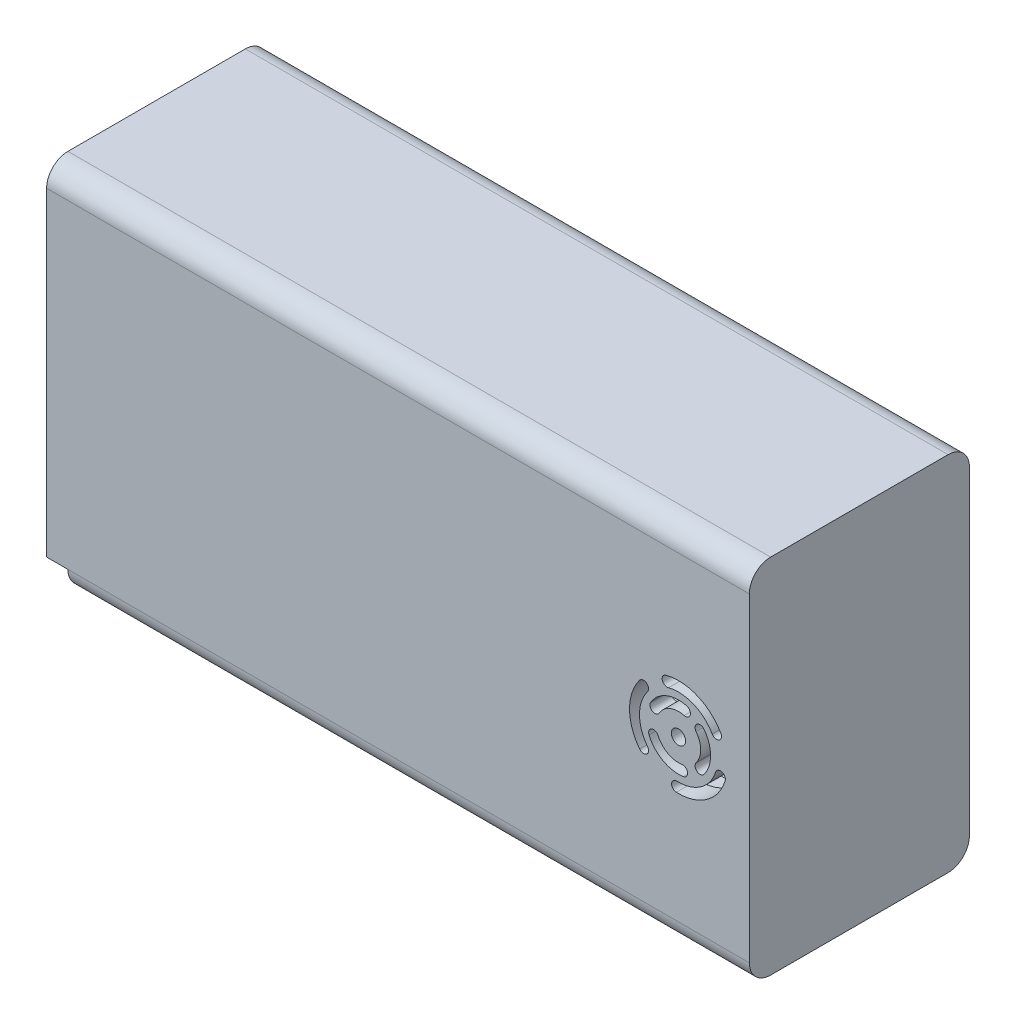
SolidWorks part; units mm, degrees
ref_plane "Front Plane" through (0, 0, 0) normal (0, 0, 1) x (1, 0, 0)
ref_plane "Top Plane" through (0, 0, 0) normal (0, 1, 0) x (1, 0, 0)
ref_plane "Right Plane" through (0, 0, 0) normal (1, 0, 0) x (0, 0, -1)
sketch "Sketch1" plane through (0, 0, 0) normal (0, 0, 1) x (1, 0, 0)
  line L1 (-49.5, 25.5) -> (49.5, 25.5)
  line L2 (-49.5, 25.5) -> (-49.5, -25.5)
  line L3 (-49.5, -25.5) -> (49.5, -25.5)
  line L4 (49.5, 25.5) -> (49.5, -25.5)
  line L5 (-49.5, 25.5) -> (49.5, -25.5) construction
  line L6 (-49.5, -25.5) -> (49.5, 25.5) construction
  point P0 (0, 0)
  dimension "D1" = 51
  dimension "D2" = 99
extrude "Boss-Extrude2" add sketch "Sketch1" along normal blind 31
sketch "Sketch3" plane through (-49.5, 0, 0) normal (-1, 0, 0) x (0, 0, 1)
  line L0 (31, -25.5) -> (0, -25.5) construction
  line L1 (3, 0.6165) -> (3, -22.5)
  line L2 (3, -22.5) -> (28, -22.5)
  line L3 (28, -22.5) -> (28, 22.5)
  line L4 (28, 22.5) -> (3, 22.5)
  line L5 (3, 22.5) -> (3, 0.6165)
  line L6 (31, 25.5) -> (0, 25.5) construction
  line L7 (31, 25.5) -> (31, -25.5) construction
  line L8 (0, 25.5) -> (0, -25.5) construction
  dimension "D1" = 3
  dimension "D2" = 3
  dimension "D3" = 3
  dimension "D4" = 3
extrude "Cut-Extrude1" cut sketch "Sketch3" against normal blind 96
sketch "Sketch4" plane through (0, -25.5, 0) normal (0, -1, 0) x (1, 0, 0)
  line L0 (-49.5, 31) -> (-46.5, 31)
  line L1 (-49.5, 31) -> (49.5, 31) construction
  line L2 (-46.5, 31) -> (-46.5, 0)
  line L3 (-49.5, 0) -> (49.5, 0) construction
  line L4 (-46.5, 0) -> (-49.5, 0)
  line L5 (-49.5, 0) -> (-49.5, 31)
extrude "Cut-Extrude2" cut sketch "Sketch4" against normal blind 3
sketch "Sketch6" plane through (-46.5, 0, 0) normal (-1, 0, 0) x (0, 0, 1)
  line L0 (15.5, -22.5) -> (15.5, 22.5) construction
  line L1 (3, -22.5) -> (28, -22.5) construction
  line L2 (28, 22.5) -> (3, 22.5) construction
  line L3 (15.5, -22.5) -> (16.8, -22.5)
  line L4 (16.8, -22.5) -> (18.8, -22.5)
  line L5 (18.8, -22.5) -> (18.8, -20.5)
  line L6 (18.8, -20.5) -> (16.8, -20.5)
  line L7 (16.8, -20.5) -> (16.8, -22.5)
  line L8 (14.2, -20.5) -> (14.2, -22.5)
  line L9 (12.2, -20.5) -> (14.2, -20.5)
  line L10 (12.2, -22.5) -> (12.2, -20.5)
  line L11 (14.2, -22.5) -> (12.2, -22.5)
  line L12 (0, 0) -> (24.4471, 0) construction
  line L13 (14.2, 22.5) -> (12.2, 22.5)
  line L14 (12.2, 22.5) -> (12.2, 20.5)
  line L15 (12.2, 20.5) -> (14.2, 20.5)
  line L16 (14.2, 20.5) -> (14.2, 22.5)
  line L17 (16.8, 20.5) -> (16.8, 22.5)
  line L18 (18.8, 20.5) -> (16.8, 20.5)
  line L19 (18.8, 22.5) -> (18.8, 20.5)
  line L20 (16.8, 22.5) -> (18.8, 22.5)
  line L21 (15.5, 22.5) -> (16.8, 22.5)
  line M14 (28, -22.5) -> (3, -22.5)
extrude "Boss-Extrude3" add sketch "Sketch6" against normal blind 96 contours L10 L8 L9 M14 | L6 L7 L5 M14 | L15 L16 L13 L14 | L20 L17 L18 L19
sketch "Sketch7" plane through (0, -22.5, 0) normal (0, -1, 0) x (1, 0, 0)
  line L0 (-49.5, 28) -> (-48.5551, 28)
  line L1 (-46.5, 28) -> (-49.5, 28) construction
  line L2 (-48.5551, 28) -> (-48.5551, 29)
  line L3 (-48.5551, 29) -> (-47.5551, 29)
  line L4 (-47.5551, 29) -> (-47.5551, 28)
  line L5 (46.5, 28) -> (-49.5, 28) construction
  line L6 (-47.5551, 28) -> (-48.5551, 28)
  line L7 (-49.5, 15.5) -> (-38.7311, 15.5) construction
  line L8 (-49.5, 28) -> (-49.5, 3) construction
  line L9 (-47.5551, 3) -> (-48.5551, 3)
  line L10 (-47.5551, 2) -> (-47.5551, 3)
  line L11 (-48.5551, 2) -> (-47.5551, 2)
  line L12 (-48.5551, 3) -> (-48.5551, 2)
  line L13 (-49.5, 3) -> (-48.5551, 3)
  line M6 (-49.5, 28) -> (-46.5, 28)
  dimension "D1" = 1
extrude "Cut-Extrude3" cut sketch "Sketch7" against normal blind 45 contours L4 L3 L2 M6 | L9 L12 L11 L10
fillet "Fillet1" radius 3 4 edges at (0, 25.5, 31) (1.5, -25.5, 31) (1.5, -25.5, 0) (0, 25.5, 0)
sketch "Sketch8" plane through (0, 0, 31) normal (0, 0, 1) x (1, 0, 0)
  line L0 (49.5, 0) -> (46.5, 0) construction
  line L1 (49.5, -22.5) -> (49.5, 22.5) construction
  line L2 (46.5, 0) -> (46.5, -34.082) construction
sketch "Sketch9" plane through (0, 0, 28) normal (0, 0, -1) x (-1, 0, 0)
  line L0 (-46.5, 0) -> (-32.4364, 0) construction
  line L1 (31.9682, -7.5) -> (46.9682, 7.5) construction
  line L2 (46.9682, -7.5) -> (31.9682, 7.5) construction
  line L3 (39.4682, -13.2796) -> (39.4682, 13.2796) construction
  line L4 (39.4682, 0) -> (32.0276, -8.8673) construction
  line L5 (39.4682, 0) -> (30.6584, 10.4992) construction
  line L6 (39.4682, 0) -> (29.0284, -4.8681) construction
  line L7 (39.4682, 0) -> (29.0284, 4.8681) construction
  line L8 (39.4682, 0) -> (48.2781, 10.4992) construction
  line L9 (39.4682, 0) -> (49.908, 4.8681) construction
  line L10 (39.4682, 0) -> (49.908, -4.8681) construction
  line L11 (39.4682, 0) -> (46.9088, -8.8673) construction
  line L12 (39.4682, 0) -> (42.9165, -12.8691) construction
  line L13 (39.4682, 0) -> (36.0199, -12.8691) construction
  line L14 (39.4682, 0) -> (42.9165, 12.8691) construction
  line L15 (39.4682, 0) -> (36.0199, 12.8691) construction
  line L16 (39.4682, 0) -> (33.744, 10.9961) construction
  line L17 (39.4682, 0) -> (45.1924, 10.9961) construction
  line L18 (39.4682, 0) -> (42.9165, -12.8691) construction
  line L19 (39.4682, 0) -> (33.744, -10.9961) construction
  line L20 (39.4682, 0) -> (45.1924, 10.9961) construction
  line L21 (39.4682, 0) -> (33.744, -10.9961) construction
  line L22 (39.4682, 0) -> (49.6763, -2.2631) construction
  line L23 (39.4682, 0) -> (47.8665, -6.4442) construction
  line L24 (39.4682, 0) -> (31.6838, 5.9732) construction
  line L25 (39.4682, 0) -> (37.2138, -1.7299) construction
  line L26 (39.4682, 0) -> (48.9178, 2.0949) construction
  line L27 (39.4682, 0) -> (49.4833, 1.0968) construction
  line L28 (39.4682, 0) -> (48.4675, 6.9054) construction
  line L29 (39.4682, 0) -> (31.4522, 1.7771) construction
  line L30 (-47.0152, -7.4485) -> (-32.0152, 7.5515) construction
  line L31 (-32.0152, -7.4485) -> (-47.0152, 7.5515) construction
  line L32 (-39.5152, -13.2282) -> (-39.5152, 13.3311) construction
  line L33 (-39.5152, 0.0515) -> (-46.9557, -8.8159) construction
  line L34 (-39.5152, 0.0515) -> (-48.325, 10.5506) construction
  line L35 (-39.5152, 0.0515) -> (-49.955, -4.8167) construction
  line L36 (-39.5152, 0.0515) -> (-49.955, 4.9196) construction
  line L37 (-39.5152, 0.0515) -> (-30.7053, 10.5506) construction
  line L38 (-39.5152, 0.0515) -> (-29.0754, 4.9196) construction
  line L39 (-39.5152, 0.0515) -> (-29.0754, -4.8167) construction
  line L40 (-39.5152, 0.0515) -> (-32.0746, -8.8159) construction
  line L41 (-39.5152, 0.0515) -> (-36.0669, -12.8177) construction
  line L42 (-39.5152, 0.0515) -> (-42.9635, -12.8177) construction
  line L43 (-39.5152, 0.0515) -> (-36.0669, 12.9206) construction
  line L44 (-39.5152, 0.0515) -> (-42.9635, 12.9206) construction
  line L45 (-39.5152, 0.0515) -> (-45.2394, 11.0475) construction
  line L46 (-39.5152, 0.0515) -> (-33.791, 11.0475) construction
  line L47 (-39.5152, 0.0515) -> (-36.0669, -12.8177) construction
  line L48 (-39.5152, 0.0515) -> (-45.2394, -10.9446) construction
  line L49 (-39.5152, 0.0515) -> (-33.791, 11.0475) construction
  line L50 (-39.5152, 0.0515) -> (-45.2394, -10.9446) construction
  line L51 (-39.5152, 0.0515) -> (-29.3071, -2.2116) construction
  line L52 (-39.5152, 0.0515) -> (-31.1169, -6.3928) construction
  line L53 (-39.5152, 0.0515) -> (-47.2996, 6.0247) construction
  line L54 (-39.5152, 0.0515) -> (-41.7696, -1.6784) construction
  line L55 (-39.5152, 0.0515) -> (-30.0656, 2.1464) construction
  line L56 (-39.5152, 0.0515) -> (-29.5001, 1.1483) construction
  line L57 (-39.5152, 0.0515) -> (-30.5159, 6.9568) construction
  line L58 (-39.5152, 0.0515) -> (-47.5312, 1.8286) construction
  circle A0 centre (39.4682, 0) radius 0.5
  circle A1 centre (39.4682, 0) radius 2
  circle A2 centre (39.4682, 0) radius 2.5
  circle A3 centre (39.4682, 0) radius 1.5
  circle A4 centre (39.4682, 0) radius 1
  arc A5 (36.4314, 2.3302) -> (36.4314, -2.3302) centre (39.4682, 0) ccw construction
  arc A6 (35.876, 2.7564) -> (35.876, -2.7564) centre (39.4682, 0) ccw
  arc A7 (36.9867, 1.9041) -> (36.9867, -1.9041) centre (39.4682, 0) ccw
  arc A8 (36.9867, 1.9041) -> (35.876, 2.7564) centre (36.4314, 2.3302) ccw
  arc A9 (35.876, -2.7564) -> (36.9867, -1.9041) centre (36.4314, -2.3302) ccw
  arc A10 (38.4775, 3.6974) -> (42.7832, 1.9139) centre (39.4682, 0) cw construction
  arc A11 (38.2963, 4.3735) -> (43.3894, 2.2639) centre (39.4682, 0) cw
  arc A12 (38.6587, 3.0212) -> (42.177, 1.5639) centre (39.4682, 0) cw
  arc A13 (38.6587, 3.0212) -> (38.2963, 4.3735) centre (38.4775, 3.6974) cw
  arc A14 (43.3894, 2.2639) -> (42.177, 1.5639) centre (42.7832, 1.9139) cw
  arc A15 (38.8859, -3.7833) -> (42.9719, -1.5416) centre (39.4682, 0) ccw construction
  arc A16 (38.7794, -4.4751) -> (43.6126, -1.8236) centre (39.4682, 0) ccw
  arc A17 (38.9924, -3.0914) -> (42.3311, -1.2597) centre (39.4682, 0) ccw
  arc A18 (38.9924, -3.0914) -> (38.7794, -4.4751) centre (38.8859, -3.7833) ccw
  arc A19 (43.6126, -1.8236) -> (42.3311, -1.2597) centre (42.9719, -1.5416) ccw
  arc A20 (44.382, 3.7704) -> (44.382, -3.7704) centre (39.4682, 0) cw construction
  arc A21 (44.9373, -4.1966) -> (44.9373, 4.1966) centre (39.4682, 0) ccw
  arc A22 (43.8266, -3.3443) -> (43.8266, 3.3443) centre (39.4682, 0) ccw
  arc A23 (43.8266, -3.3443) -> (44.9373, -4.1966) centre (44.382, -3.7704) ccw
  arc A24 (44.9373, 4.1966) -> (43.8266, 3.3443) centre (44.382, 3.7704) ccw
  arc A25 (33.5612, -1.8625) -> (39.7384, -6.1877) centre (39.4682, 0) ccw construction
  arc A26 (39.7689, -6.8871) -> (32.8936, -2.073) centre (39.4682, 0) cw
  arc A27 (39.7078, -5.4884) -> (34.2288, -1.652) centre (39.4682, 0) cw
  arc A28 (39.7078, -5.4884) -> (39.7689, -6.8871) centre (39.7384, -6.1877) cw
  arc A29 (32.8936, -2.073) -> (34.2288, -1.652) centre (33.5612, -1.8625) cw
  arc A30 (34.1044, 3.0968) -> (41.0712, 5.9826) centre (39.4682, 0) cw construction
  arc A31 (41.2524, 6.6587) -> (33.4981, 3.4468) centre (39.4682, 0) ccw
  arc A32 (40.8901, 5.3064) -> (34.7106, 2.7468) centre (39.4682, 0) ccw
  arc A33 (40.8901, 5.3064) -> (41.2524, 6.6587) centre (41.0712, 5.9826) ccw
  arc A34 (33.4981, 3.4468) -> (34.7106, 2.7468) centre (34.1044, 3.0968) ccw
  circle A35 centre (-39.5152, 0.0515) radius 0.5
  circle A36 centre (-39.5152, 0.0515) radius 2
  circle A37 centre (-39.5152, 0.0515) radius 2.5
  circle A38 centre (-39.5152, 0.0515) radius 1.5
  circle A39 centre (-39.5152, 0.0515) radius 1
  arc A40 (-42.552, 2.3817) -> (-42.552, -2.2788) centre (-39.5152, 0.0515) ccw construction
  arc A41 (-43.1073, 2.8078) -> (-43.1073, -2.7049) centre (-39.5152, 0.0515) ccw
  arc A42 (-41.9967, 1.9556) -> (-41.9967, -1.8526) centre (-39.5152, 0.0515) ccw
  arc A43 (-41.9967, 1.9556) -> (-43.1073, 2.8078) centre (-42.552, 2.3817) ccw
  arc A44 (-43.1073, -2.7049) -> (-41.9967, -1.8526) centre (-42.552, -2.2788) ccw
  arc A45 (-40.5059, 3.7488) -> (-36.2002, 1.9654) centre (-39.5152, 0.0515) cw construction
  arc A46 (-40.6871, 4.425) -> (-35.594, 2.3154) centre (-39.5152, 0.0515) cw
  arc A47 (-40.3247, 3.0727) -> (-36.8064, 1.6154) centre (-39.5152, 0.0515) cw
  arc A48 (-40.3247, 3.0727) -> (-40.6871, 4.425) centre (-40.5059, 3.7488) cw
  arc A49 (-35.594, 2.3154) -> (-36.8064, 1.6154) centre (-36.2002, 1.9654) cw
  arc A50 (-40.0975, -3.7318) -> (-36.0115, -1.4902) centre (-39.5152, 0.0515) ccw construction
  arc A51 (-40.204, -4.4237) -> (-35.3708, -1.7721) centre (-39.5152, 0.0515) ccw
  arc A52 (-39.991, -3.04) -> (-36.6523, -1.2083) centre (-39.5152, 0.0515) ccw
  arc A53 (-39.991, -3.04) -> (-40.204, -4.4237) centre (-40.0975, -3.7318) ccw
  arc A54 (-35.3708, -1.7721) -> (-36.6523, -1.2083) centre (-36.0115, -1.4902) ccw
  arc A55 (-34.6014, 3.8219) -> (-34.6014, -3.719) centre (-39.5152, 0.0515) cw construction
  arc A56 (-34.0461, -4.1451) -> (-34.0461, 4.248) centre (-39.5152, 0.0515) ccw
  arc A57 (-35.1568, -3.2929) -> (-35.1568, 3.3958) centre (-39.5152, 0.0515) ccw
  arc A58 (-35.1568, -3.2929) -> (-34.0461, -4.1451) centre (-34.6014, -3.719) ccw
  arc A59 (-34.0461, 4.248) -> (-35.1568, 3.3958) centre (-34.6014, 3.8219) ccw
  arc A60 (-45.4222, -1.811) -> (-39.245, -6.1363) centre (-39.5152, 0.0515) ccw construction
  arc A61 (-39.2145, -6.8356) -> (-46.0898, -2.0215) centre (-39.5152, 0.0515) cw
  arc A62 (-39.2756, -5.437) -> (-44.7546, -1.6005) centre (-39.5152, 0.0515) cw
  arc A63 (-39.2756, -5.437) -> (-39.2145, -6.8356) centre (-39.245, -6.1363) cw
  arc A64 (-46.0898, -2.0215) -> (-44.7546, -1.6005) centre (-45.4222, -1.811) cw
  arc A65 (-44.879, 3.1483) -> (-37.9122, 6.0341) centre (-39.5152, 0.0515) cw construction
  arc A66 (-37.731, 6.7102) -> (-45.4853, 3.4983) centre (-39.5152, 0.0515) ccw
  arc A67 (-38.0933, 5.3579) -> (-44.2728, 2.7983) centre (-39.5152, 0.0515) ccw
  arc A68 (-38.0933, 5.3579) -> (-37.731, 6.7102) centre (-37.9122, 6.0341) ccw
  arc A69 (-45.4853, 3.4983) -> (-44.2728, 2.7983) centre (-44.879, 3.1483) ccw
  point P4 (-39.5152, 0.0515)
  point P5 (39.4682, 0)
  point P32 (35.6404, 0)
  point P45 (40.9331, 3.5364)
  point P56 (41.3093, -3.356)
  point P64 (45.6618, 0)
  point P71 (35.9157, -5.0735)
  point P80 (37.098, 5.7222)
  point P85 (39.4682, 0.5)
  point P112 (-43.343, 0.0515)
  point P125 (-38.0503, 3.5879)
  point P136 (-37.674, -3.3045)
  point P144 (-33.3215, 0.0515)
  point P151 (-43.0677, -5.0221)
  point P160 (-41.8854, 5.7736)
  point P165 (-39.5152, 0.5515)
  dimension "D2" = 5
  dimension "D3" = 4
  dimension "D4" = 3
  dimension "D5" = 2
  dimension "D6" = 1
  dimension "D13" = 0.7
  dimension "D14" = 0.7
  dimension "D16" = 5
  dimension "D17" = 4
  dimension "D18" = 3
  dimension "D19" = 2
  dimension "D20" = 1
  dimension "D27" = 0.7
  dimension "D28" = 0.7
  dimension "D1" = 15
  dimension "D7" = 25
  dimension "D8" = 12.5
  dimension "D9" = 12.5
  dimension "D10" = 12.5
  dimension "D11" = 6.25
  dimension "D12" = 12.5
  dimension "D15" = 15
  dimension "D21" = 25
  dimension "D22" = 12.5
  dimension "D23" = 12.5
  dimension "D24" = 12.5
  dimension "D25" = 6.25
  dimension "D26" = 12.5
extrude "Cut-Extrude4" cut sketch "Sketch9" against normal blind 10 contours A41 A44 A42 A43 | A66 A69 A67 A68 | A49 A46 A48 A47 | A56 A59 A57 A58 | A51 A54 A52 A53 | A64 A61 A63 A62 | A35 | A39 A35
